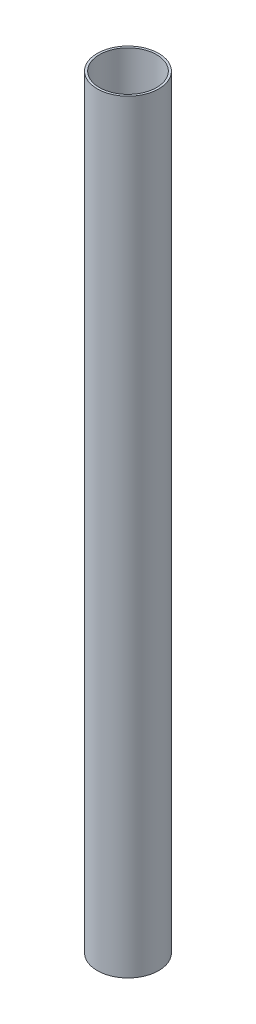
SolidWorks part; units mm, degrees
ref_plane "Front Plane" through (0, 0, 0) normal (0, 0, 1) x (1, 0, 0)
ref_plane "Top Plane" through (0, 0, 0) normal (0, 1, 0) x (1, 0, 0)
ref_plane "Right Plane" through (0, 0, 0) normal (1, 0, 0) x (0, 0, -1)
sketch "Sketch1" plane through (0, 0, 0) normal (0, 1, 0) x (1, 0, 0)
  circle A0 centre (0, 0) radius 19.05
  dimension "D1" = 38.1
extrude "Extrude-Thin1" add sketch "Sketch1" along normal blind 473.202 thin thin type one direction reverse wall 1.3513
